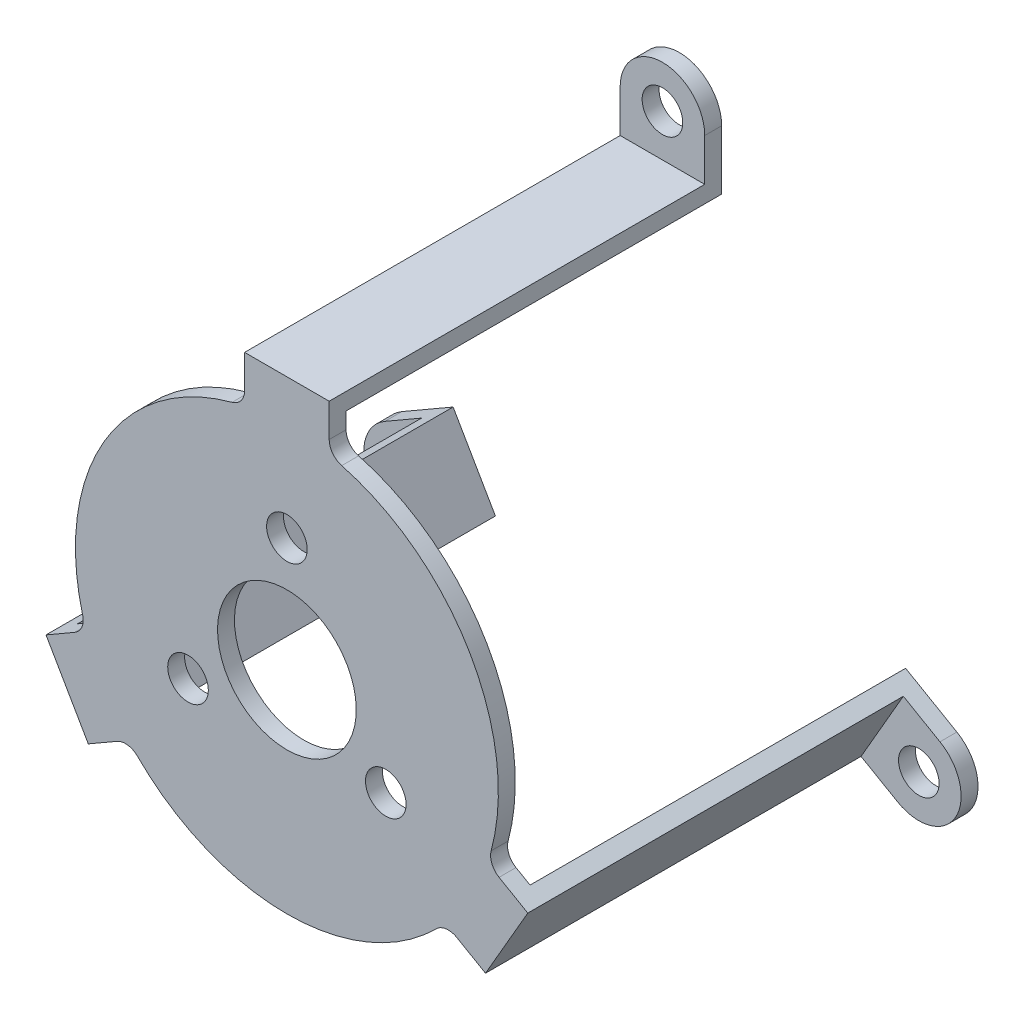
SolidWorks part; units mm, degrees
material "Liga 6061"
ref_plane "Plano frontal" through (0, 0, 0) normal (0, 0, 1) x (1, 0, 0)
ref_plane "Plano superior" through (0, 0, 0) normal (0, 1, 0) x (1, 0, 0)
ref_plane "Plano direito" through (0, 0, 0) normal (1, 0, 0) x (0, 0, -1)
sketch "Esboço1" plane through (0, 0, 0) normal (0, 1, 0) x (1, 0, 0)
  line L0 (0, 0) -> (0, -35.0841) construction
  line L1 (-2.5, 15) -> (-2.5, 12.2474)
  line L2 (2.5, 15) -> (2.5, 12.2474)
  line L3 (14.2404, -5.3349) -> (11.8566, -3.9587)
  line L4 (11.7404, -9.6651) -> (9.3566, -8.2888)
  line L5 (-11.7404, -9.6651) -> (-9.3566, -8.2888)
  line L6 (-14.2404, -5.3349) -> (-11.8566, -3.9587)
  line L7 (-2.5, 15) -> (2.5, 15)
  line L8 (14.2404, -5.3349) -> (11.7404, -9.6651)
  line L9 (-11.7404, -9.6651) -> (-14.2404, -5.3349)
  circle A0 centre (0, 0) radius 4.1
  circle A1 centre (0, 0) radius 6.75 construction
  arc A2 (-9.3566, -8.2888) -> (9.3566, -8.2888) centre (0, 0) ccw
  circle A4 centre (0, 6.75) radius 1.2
  circle A5 centre (5.8457, -3.375) radius 1.2
  circle A6 centre (-5.8457, -3.375) radius 1.2
  arc A8 (11.8566, -3.9587) -> (2.5, 12.2474) centre (0, 0) ccw
  arc A10 (-2.5, 12.2474) -> (-11.8566, -3.9587) centre (0, 0) ccw
  point P17 (0, 0)
  point P29 (0, 0)
  dimension "D1" = 3
  dimension "D2" = 8.2
  dimension "D3" = 2.4
  dimension "D4" = 13.5
  dimension "D7" = 15
  dimension "D8" = 12.5
  dimension "D6" = 5
  dimension "D5" = 3
extrude "Ressalto-extrusão1" add sketch "Esboço1" along normal blind 1
sketch "Esboço2" plane through (0, 0, 0) normal (0, -1, 0) x (1, 0, 0)
  line L0 (-11.7404, 9.6651) -> (-9.3566, 8.2888) construction
  line L1 (-11.8566, 3.9587) -> (-14.2404, 5.3349) construction
  line L2 (-2.5, -15) -> (-2.5, -12.2474) construction
  line L3 (2.5, -12.2474) -> (2.5, -15) construction
  line L4 (14.2404, 5.3349) -> (11.8566, 3.9587) construction
  line L5 (9.3566, 8.2888) -> (11.7404, 9.6651) construction
  line L6 (-11.7404, 9.6651) -> (-10.8744, 9.1651)
  line L7 (-13.3744, 4.8349) -> (-14.2404, 5.3349)
  line L8 (-2.5, -15) -> (-2.5, -14)
  line L9 (2.5, -14) -> (2.5, -15)
  line L10 (14.2404, 5.3349) -> (13.3744, 4.8349)
  line L11 (10.8744, 9.1651) -> (11.7404, 9.6651)
  line L12 (-14.2404, 5.3349) -> (-11.7404, 9.6651) construction
  line L13 (11.7404, 9.6651) -> (14.2404, 5.3349) construction
  line L14 (2.5, -15) -> (-2.5, -15) construction
  line L15 (-14.2404, 5.3349) -> (-11.7404, 9.6651)
  line L16 (11.7404, 9.6651) -> (14.2404, 5.3349)
  line L17 (2.5, -15) -> (-2.5, -15)
  line L18 (-13.3744, 4.8349) -> (-10.8744, 9.1651)
  line L19 (2.5, -14) -> (-2.5, -14)
  line L20 (10.8744, 9.1651) -> (13.3744, 4.8349)
  line L21 (1.5, -14) -> (-1.5, -14) construction
  line L22 (-1.5, -14) -> (-1.5, -13.9852) construction
  line L23 (1.5, -13.9852) -> (1.5, -14) construction
  line L24 (-2.5, -15) -> (-2.5, -13.9852) construction
  line L25 (2.5, -13.9852) -> (2.5, -15) construction
  line M4 (2.5, -15) -> (2.5, -12.2474)
  line M8 (11.7404, 9.6651) -> (9.3566, 8.2888)
  line M12 (-14.2404, 5.3349) -> (-11.8566, 3.9587)
  line M29 (-2.5, -15) -> (2.5, -15)
  line M30 (14.2404, 5.3349) -> (11.7404, 9.6651)
  line M31 (-11.7404, 9.6651) -> (-14.2404, 5.3349)
  dimension "D1" = 1
  dimension "D2" = 1
  dimension "D3" = 1
extrude "Ressalto-extrusão2" add sketch "Esboço2" along normal blind 22.2 contours L19 L8 M4 M29 | L18 L6 M12 M31 | L20 L10 M8 M30
sketch "Esboço3" plane through (0, -22.2, 0) normal (0, -1, 0) x (1, 0, 0)
  line L0 (2.5, -15) -> (2.5, -17.5)
  line L1 (-2.5, -15) -> (-2.5, -17.5)
  line L2 (-11.7404, 9.6651) -> (-13.9054, 10.9151)
  line L3 (-14.2404, 5.3349) -> (-16.4054, 6.5849)
  line L4 (14.2404, 5.3349) -> (16.4054, 6.5849)
  line L5 (11.7404, 9.6651) -> (13.9054, 10.9151)
  line L6 (-2.5, -15) -> (2.5, -15) construction
  line L7 (-2.5, -15) -> (2.5, -15)
  line L8 (-11.7404, 9.6651) -> (-14.2404, 5.3349) construction
  line L9 (-11.7404, 9.6651) -> (-14.2404, 5.3349)
  line L10 (14.2404, 5.3349) -> (11.7404, 9.6651) construction
  line L11 (14.2404, 5.3349) -> (11.7404, 9.6651)
  circle A2 centre (0, -17.5) radius 1.2
  arc A3 (-2.5, -17.5) -> (2.5, -17.5) centre (0, -17.5) ccw
  circle A5 centre (-15.1554, 8.75) radius 1.2
  arc A6 (-13.9054, 10.9151) -> (-16.4054, 6.5849) centre (-15.1554, 8.75) ccw
  circle A8 centre (15.1554, 8.75) radius 1.2
  arc A9 (16.4054, 6.5849) -> (13.9054, 10.9151) centre (15.1554, 8.75) ccw
  point P21 (0, 0)
  dimension "D2" = 17.5
  dimension "D3" = 2.4
  dimension "D1" = 3
extrude "Ressalto-extrusão3" add sketch "Esboço3" against normal blind 1
fillet "Filete1" radius 1 6 edges at (11.8566, 0.5, 3.9587) (2.5, 0.5, -12.2474) (-2.5, 0.5, -12.2474) (-11.8566, 0.5, 3.9587) (9.3566, 0.5, 8.2888) (-9.3566, 0.5, 8.2888)
split "Split1" [suppressed] bodies to split 103
move or copy body "Body-Move/Copy1" [suppressed] bodies to move or copy 103 103 103 103 copy no rotation origin (0, -10.6, -3.75) rotation axis (1, 0, 0) rotation angle 90
move or copy body "Body-Move/Copy2" bodies to move or copy 103 copy no rotation origin (0, -10.6, -3.75) rotation axis (1, 0, 0) rotation angle 90
